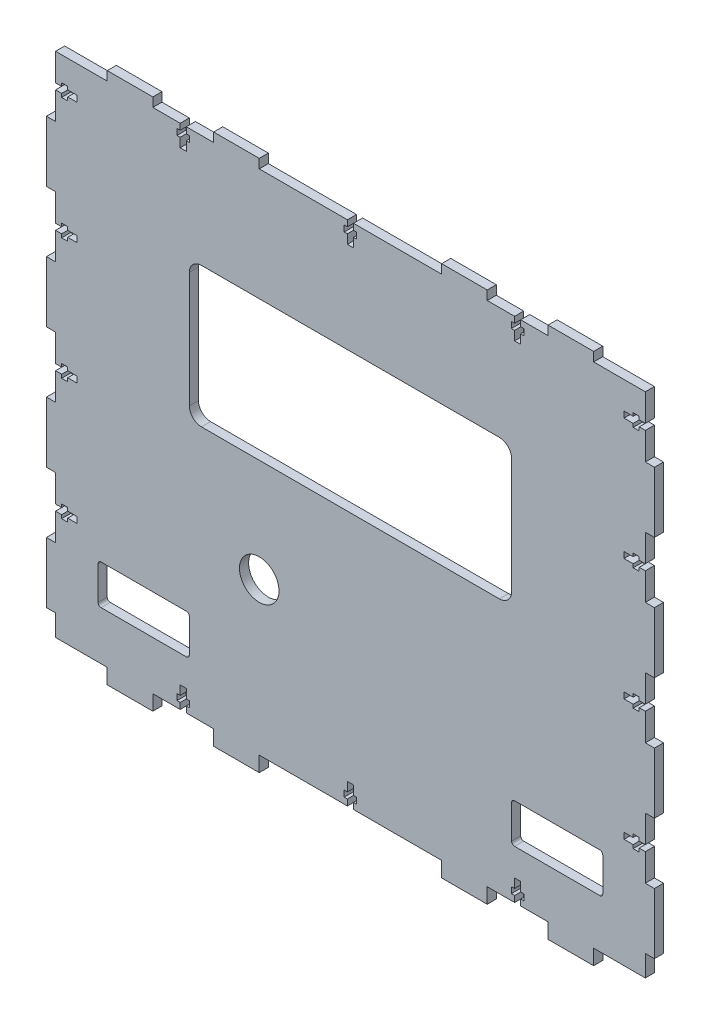
SolidWorks part; units mm, degrees
ref_plane "Front" through (0, 0, 0) normal (0, 0, 1) x (1, 0, 0)
ref_plane "Top" through (0, 0, 0) normal (0, 1, 0) x (1, 0, 0)
ref_plane "Right" through (0, 0, 0) normal (1, 0, 0) x (0, 0, -1)
sketch "草图1" plane through (0, 0, 0) normal (0, 0, 1) x (1, 0, 0)
  line L1 (0, 0) -> (200, 0)
  line L2 (0, 0) -> (0, 175)
  line L3 (0, 175) -> (200, 175)
  line L4 (200, 0) -> (200, 175)
  dimension "D1" = 175
  dimension "D2" = 200
extrude "凸台-拉伸1" add sketch "草图1" along normal blind 3
sketch "草图2" plane through (0, 0, 3) normal (0, 0, 1) x (1, 0, 0)
  line L0 (200, 175) -> (0, 175) construction
  line L1 (0, 175) -> (20, 175)
  line L2 (0, 175) -> (0, 172)
  line L3 (0, 172) -> (20, 172)
  line L4 (20, 175) -> (20, 172)
  line L5 (200, 175) -> (180, 175)
  line L6 (200, 175) -> (200, 172)
  line L7 (200, 172) -> (180, 172)
  line L8 (180, 175) -> (180, 172)
  line L9 (35, 175) -> (55, 175)
  line L10 (35, 175) -> (35, 172)
  line L11 (35, 172) -> (55, 172)
  line L12 (55, 175) -> (55, 172)
  line L14 (165, 175) -> (145, 175)
  line L15 (165, 175) -> (165, 172)
  line L16 (165, 172) -> (145, 172)
  line L17 (145, 175) -> (145, 172)
  line L18 (70, 175) -> (130, 175)
  line L19 (70, 175) -> (70, 172)
  line L20 (70, 172) -> (130, 172)
  line L21 (130, 175) -> (130, 172)
  dimension "D1" = 3
  dimension "D2" = 20
  dimension "D3" = 20
  dimension "D4" = 3
  dimension "D5" = 3
  dimension "D6" = 20
  dimension "D7" = 15
  dimension "D8" = 3
  dimension "D9" = 20
  dimension "D10" = 15
  dimension "D11" = 15
  dimension "D12" = 15
extrude "切除-拉伸1" cut sketch "草图2" against normal through all
ref_plane "基准面1" through (0, 87.5, 0) normal (0, -1, 0) x (-1, 0, 0)
mirror "镜向1" about plane through (0, 87.5, 0) normal (0, -1, 0) of "切除-拉伸1"
sketch "草图3" plane through (0, 0, 3) normal (0, 0, 1) x (1, 0, 0)
  line L1 (0, 172) -> (3, 172)
  line L2 (0, 172) -> (0, 152)
  line L3 (0, 152) -> (3, 152)
  line L4 (3, 172) -> (3, 152)
  line L5 (200, 172) -> (197, 172)
  line L6 (200, 172) -> (200, 152)
  line L7 (200, 152) -> (197, 152)
  line L8 (197, 172) -> (197, 152)
  dimension "D1" = 20
  dimension "D2" = 3
  dimension "D3" = 3
  dimension "D4" = 20
extrude "切除-拉伸2" cut sketch "草图3" against normal through all
pattern_linear "阵列(线性)1" count 5 spacing 40 along (0, -1, 0) of "切除-拉伸2"
sketch "草图4" plane through (0, 0, 3) normal (0, 0, 1) x (1, 0, 0)
  line L0 (3, 5) -> (20, 5)
  line L1 (3, 3) -> (3, 12) construction
  line L2 (197, 12) -> (197, 3) construction
  line L3 (3, 3) -> (20, 3) construction
  line L4 (3, 5) -> (3, 3)
  line L5 (3, 3) -> (20, 3)
  line L6 (20, 3) -> (20, 5)
  line L7 (35, 3) -> (35, 5)
  line L8 (35, 3) -> (55, 3)
  line L9 (55, 3) -> (55, 5)
  line L10 (70, 5) -> (70, 3)
  line L11 (70, 3) -> (130, 3)
  line L12 (130, 3) -> (130, 5)
  line L13 (145, 5) -> (145, 3)
  line L14 (145, 3) -> (165, 3)
  line L15 (165, 3) -> (165, 5)
  line L16 (180, 5) -> (180, 3)
  line L17 (180, 3) -> (197, 3)
  line L18 (197, 3) -> (197, 5)
  line L19 (180, 5) -> (197, 5)
  line L20 (145, 5) -> (165, 5)
  line L21 (70, 5) -> (130, 5)
  line L22 (35, 5) -> (55, 5)
  dimension "D1" = 2
extrude "切除-拉伸3" cut sketch "草图4" against normal through all
sketch "草图5" plane through (0, 0, 3) normal (0, 0, 1) x (1, 0, 0)
  line L0 (70, 175) -> (55, 175) construction
  line L1 (47, 135) -> (153, 135)
  line L2 (47, 135) -> (47, 89)
  line L3 (47, 89) -> (153, 89)
  line L4 (153, 135) -> (153, 89)
  line L5 (70, 172) -> (130, 172) construction
  point P6 (100, 135)
  point P9 (100, 172)
  dimension "D1" = 46
  dimension "D2" = 106
  dimension "D3" = 40
  dimension "D4" = 0
extrude "切除-拉伸4" cut sketch "草图5" against normal through all
fillet "圆角1" radius 4 4 edges at (153, 135, 1.5) (153, 89, 1.5) (47, 89, 1.5) (47, 135, 1.5)
sketch "草图6" plane through (0, 0, 3) normal (0, 0, 1) x (1, 0, 0)
  line L0 (0, 32) -> (0, 12) construction
  line L1 (17, 34) -> (47, 34)
  line L2 (17, 34) -> (17, 21)
  line L3 (17, 21) -> (47, 21)
  line L4 (47, 34) -> (47, 21)
  line L5 (20, 0) -> (35, 0) construction
  line L6 (200, 12) -> (200, 32) construction
  line L7 (153, 34) -> (183, 34)
  line L8 (153, 34) -> (153, 21)
  line L9 (153, 21) -> (183, 21)
  line L10 (183, 34) -> (183, 21)
  line L11 (165, 0) -> (180, 0) construction
  dimension "D1" = 30
  dimension "D2" = 13
  dimension "D3" = 17
  dimension "D4" = 21
  dimension "D5" = 30
  dimension "D6" = 13
  dimension "D7" = 17
  dimension "D8" = 21
extrude "切除-拉伸5" cut sketch "草图6" against normal through all
fillet "圆角2" radius 1 8 edges at (153, 34, 1.5) (183, 34, 1.5) (183, 21, 1.5) (153, 21, 1.5) (47, 21, 1.5) (47, 34, 1.5) (17, 21, 1.5) (17, 34, 1.5)
sketch "草图7" plane through (0, 0, 3) normal (0, 0, 1) x (1, 0, 0)
  line L0 (3, 152) -> (3, 172) construction
  line L1 (5, 164.05) -> (7, 164.05)
  line L2 (5, 164.05) -> (5, 163)
  line L3 (5, 159.85) -> (7, 159.85)
  line L4 (7, 164.05) -> (7, 163)
  line L5 (3, 163) -> (5, 163)
  line L6 (3, 163) -> (3, 161)
  line L7 (3, 161) -> (5, 161)
  line L8 (10, 163) -> (10, 161)
  line L9 (7, 163) -> (10, 163)
  line L10 (7, 161) -> (7, 159.85)
  line L11 (5, 161) -> (5, 159.85)
  line L12 (7, 161) -> (10, 161)
  point P8 (3, 162)
  point P11 (3, 162)
  dimension "D1" = 4.2
  dimension "D2" = 2
  dimension "D3" = 2
  dimension "D4" = 1.05
  dimension "D5" = 0
  dimension "D6" = 2
  dimension "D7" = 7
  dimension "D8" = 0
extrude "切除-拉伸6" cut sketch "草图7" against normal through all
pattern_linear "阵列(线性)2" count 4 spacing 40 along (0, -1, 0) of "切除-拉伸6"
ref_plane "基准面2" through (100, 0, 0) normal (-1, 0, 0) x (0, 0, 1)
mirror "镜向2" about plane through (100, 0, 0) normal (-1, 0, 0) of "阵列(线性)2", "切除-拉伸6"
sketch "草图8" plane through (0, 0, 3) normal (0, 0, 1) x (1, 0, 0)
  line L1 (44, 172) -> (46, 172)
  line L2 (44, 172) -> (44, 170)
  line L3 (44, 165) -> (46, 165)
  line L4 (46, 172) -> (46, 170)
  line L5 (42.95, 170) -> (44, 170)
  line L6 (42.95, 170) -> (42.95, 168)
  line L7 (42.95, 168) -> (44, 168)
  line L8 (47.05, 170) -> (47.05, 168)
  line L9 (35, 172) -> (55, 172) construction
  line L10 (46, 170) -> (47.05, 170)
  line L11 (44, 168) -> (44, 165)
  line L12 (46, 168) -> (46, 165)
  line L13 (46, 168) -> (47.05, 168)
  point P10 (45, 172)
  point P13 (45, 172)
  dimension "D1" = 2
  dimension "D2" = 7
  dimension "D3" = 2
  dimension "D4" = 4.1
  dimension "D5" = 1.05
  dimension "D6" = 2
  dimension "D7" = 0
  dimension "D8" = 0
extrude "切除-拉伸7" cut sketch "草图8" against normal through all
pattern_linear "阵列(线性)3" count 3 spacing 55 along (1, 0, 0) of "切除-拉伸7"
ref_plane "基准面3" through (0, 88.5, 0) normal (0, 1, 0) x (1, 0, 0)
mirror "镜向3" about plane through (0, 88.5, 0) normal (0, 1, 0) of "阵列(线性)3", "切除-拉伸7"
sketch "草图9" plane through (0, 0, 3) normal (0, 0, 1) x (1, 0, 0)
  line L0 (55, 0) -> (70, 0) construction
  line L1 (0, 72) -> (0, 52) construction
  circle A0 centre (70, 55) radius 6.5
  dimension "D1" = 13
  dimension "D2" = 55
  dimension "D3" = 70
extrude "切除-拉伸8" cut sketch "草图9" against normal through all
